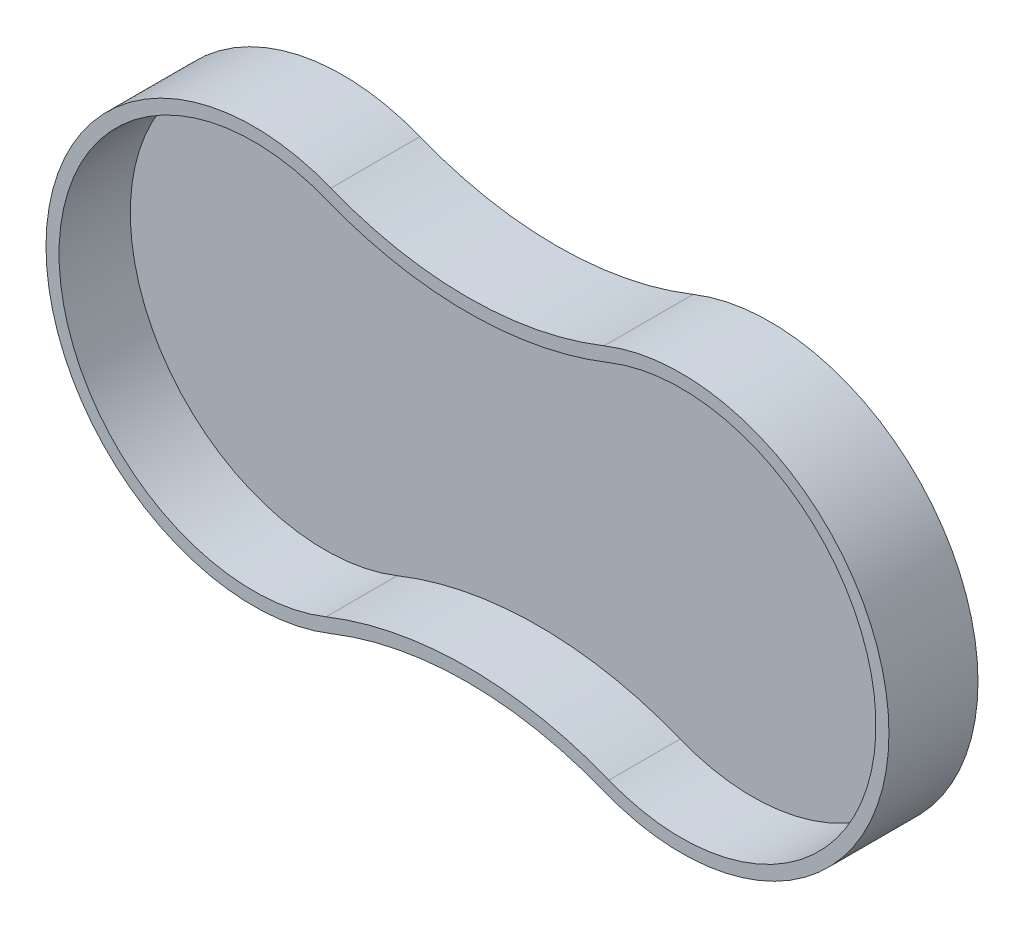
SolidWorks part; units mm, degrees
ref_plane "Front Plane" through (0, 0, 0) normal (0, 0, 1) x (1, 0, 0)
ref_plane "Top Plane" through (0, 0, 0) normal (0, 1, 0) x (1, 0, 0)
ref_plane "Right Plane" through (0, 0, 0) normal (1, 0, 0) x (0, 0, -1)
sketch "Sketch1" plane through (0, 0, 0) normal (0, 0, 1) x (1, 0, 0)
  line L0 (-36, 0) -> (36, 0) construction
  line L1 (-23.0096, 32.5) -> (23.0096, 32.5) construction
  line L2 (23.0096, 32.5) -> (23.0096, -32.5) construction
  line L3 (23.0096, -32.5) -> (-23.0096, -32.5) construction
  line L4 (-23.0096, -32.5) -> (-23.0096, 32.5) construction
  arc A0 (-23.0096, 32.5) -> (-23.0096, -32.5) centre (-36, 0) ccw
  arc A1 (23.0096, -32.5) -> (23.0096, 32.5) centre (36, 0) ccw
  arc A2 (-23.0096, 32.5) -> (23.0096, 32.5) centre (0, 90.0666) ccw
  arc A3 (-23.0096, -32.5) -> (23.0096, -32.5) centre (0, -90.0666) cw
  point P1 (0, 0)
  point P3 (-19.1784, 31.1883)
  dimension "D1" = 70
  dimension "D2" = 72
  dimension "D3" = 65
extrude "Boss-Extrude1" add sketch "Sketch1" along normal blind 15
sketch "Sketch2" plane through (0, 0, 15) normal (0, 0, 1) x (1, 0, 0)
  arc A8 (-23.8262, 30.4571) -> (23.8262, 30.4571) centre (0, 90.0666) ccw
  arc A9 (-23.8262, 30.4571) -> (-23.8262, -30.4571) centre (-36, 0) ccw
  arc A10 (23.8262, -30.4571) -> (-23.8262, -30.4571) centre (0, -90.0666) ccw
  arc A11 (23.8262, -30.4571) -> (23.8262, 30.4571) centre (36, 0) ccw
  arc A12 (-23.8262, 30.4571) -> (23.8262, 30.4571) centre (0, 90.0666) ccw
  arc A13 (-23.8262, 30.4571) -> (-23.8262, -30.4571) centre (-36, 0) ccw
  arc A14 (23.8262, -30.4571) -> (-23.8262, -30.4571) centre (0, -90.0666) ccw
  arc A15 (23.8262, -30.4571) -> (23.8262, 30.4571) centre (36, 0) ccw
  dimension "D1" = 2.2
extrude "Cut-Extrude2" cut sketch "Sketch2" against normal blind 12
